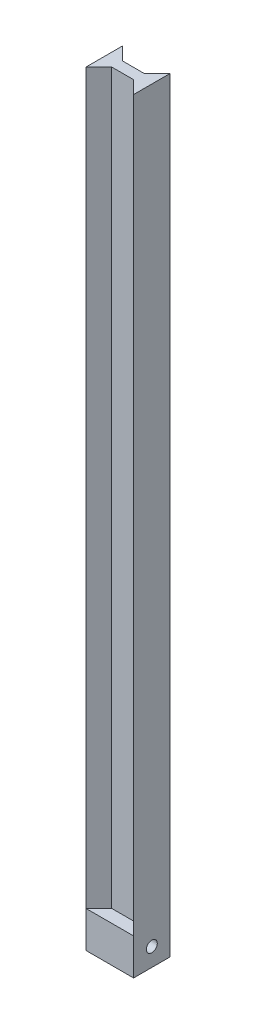
SolidWorks part; units mm, degrees
ref_plane "Front Plane" through (0, 0, 0) normal (0, 0, 1) x (1, 0, 0)
ref_plane "Top Plane" through (0, 0, 0) normal (0, 1, 0) x (1, 0, 0)
ref_plane "Right Plane" through (0, 0, 0) normal (1, 0, 0) x (0, 0, -1)
sketch "Sketch1" plane through (0, 0, 0) normal (0, 1, 0) x (1, 0, 0)
  line L0 (0, 0) -> (-3.5355, -3.5355)
  line L1 (-3.5355, -3.5355) -> (-9.5355, -3.5355)
  line L2 (-9.5355, -3.5355) -> (-13.0711, 0)
  line L3 (-13.0711, 0) -> (-13.0711, -10)
  line L4 (-13.0711, -10) -> (-9.5355, -6.4645)
  line L5 (-9.5355, -6.4645) -> (-3.5355, -6.4645)
  line L6 (-3.5355, -6.4645) -> (0, -10)
  line L7 (0, -10) -> (0, 0)
  dimension "D1" = 6
  dimension "D2" = 6
  dimension "D3" = 135
  dimension "D4" = 135
  dimension "D5" = 10
  dimension "D6" = 10
  dimension "D7" = 5
  dimension "D8" = 5
extrude "Boss-Extrude1" add sketch "Sketch1" along normal blind 200
sketch "Sketch2" plane through (0, 0, 0) normal (0, -1, 0) x (1, 0, 0)
  line L1 (0, 0) -> (-13.0711, 0)
  line L2 (0, 0) -> (0, 10)
  line L3 (0, 10) -> (-13.0711, 10)
  line L4 (-13.0711, 0) -> (-13.0711, 10)
extrude "Boss-Extrude2" add sketch "Sketch2" along normal blind 10
sketch "Sketch3" plane through (-13.0711, 0, 0) normal (-1, 0, 0) x (0, 0, 1)
  line L0 (10, -10) -> (0, -10) construction
  line L2 (0, -10) -> (0, 0) construction
  circle A0 centre (5, -5) radius 1.5
  point P4 (5, -10)
  point P7 (0, -5)
  dimension "D1" = 0
  dimension "D2" = 0
  dimension "D3" = 3
extrude "Cut-Extrude1" cut sketch "Sketch3" against normal blind 30
